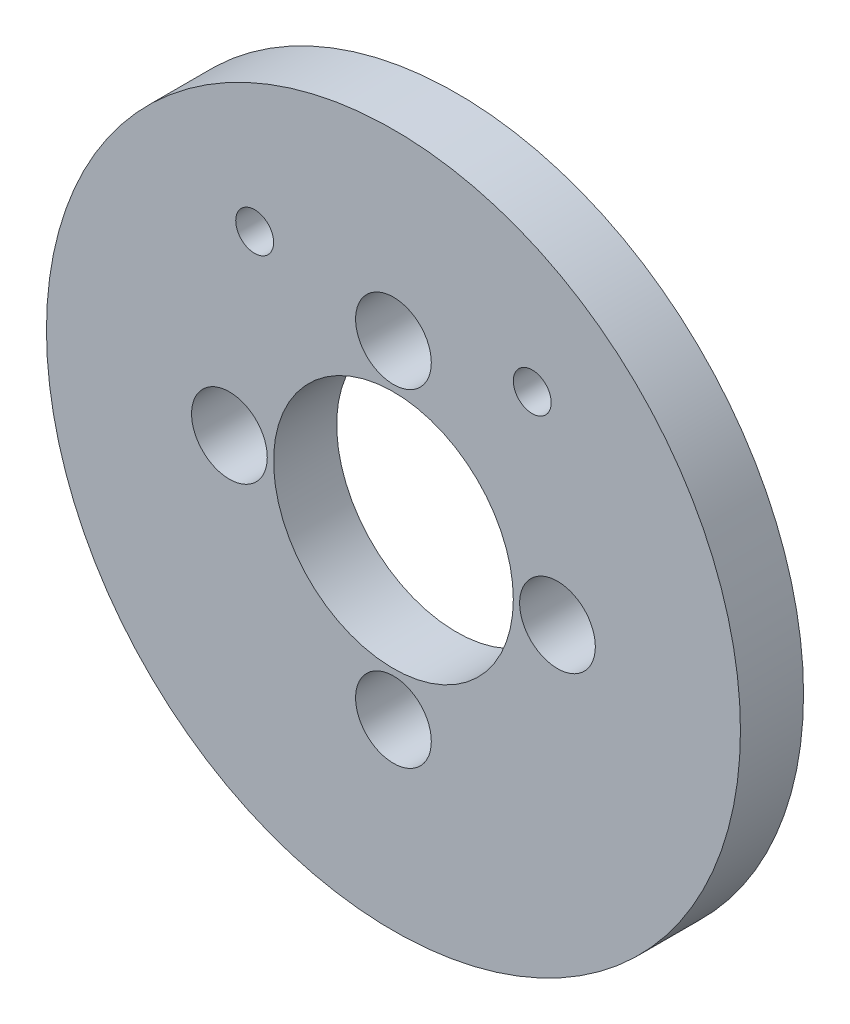
SolidWorks part; units mm, degrees
ref_plane "Plan de face" through (0, 0, 0) normal (0, 0, 1) x (1, 0, 0)
ref_plane "Plan de dessus" through (0, 0, 0) normal (0, 1, 0) x (1, 0, 0)
ref_plane "Plan de droite" through (0, 0, 0) normal (1, 0, 0) x (0, 0, -1)
sketch "Esquisse1" plane through (0, 0, 0) normal (0, 0, 1) x (1, 0, 0)
  circle A0 centre (0, 0) radius 27.5
  circle A1 centre (0, 0) radius 9.5
  dimension "D1" = 19
  dimension "D2" = 55
extrude "Boss.-Extru.1" add sketch "Esquisse1" along normal blind 5
sketch "Esquisse2" plane through (0, 0, 5) normal (0, 0, 1) x (1, 0, 0)
  line L0 (0, 0) -> (0, 36.3914) construction
  circle A0 centre (-13, 0) radius 3
  circle A1 centre (0, 13) radius 3
  circle A2 centre (13, 0) radius 3
  circle A3 centre (0, -13) radius 3
  circle A4 centre (11, 15) radius 1.5
  circle A5 centre (-11, 15) radius 1.5
  dimension "D1" = 6
  dimension "D2" = 3
  dimension "D3" = 11
  dimension "D4" = 15
extrude "Enlèv. mat.-Extru.1" cut sketch "Esquisse2" against normal blind 5
